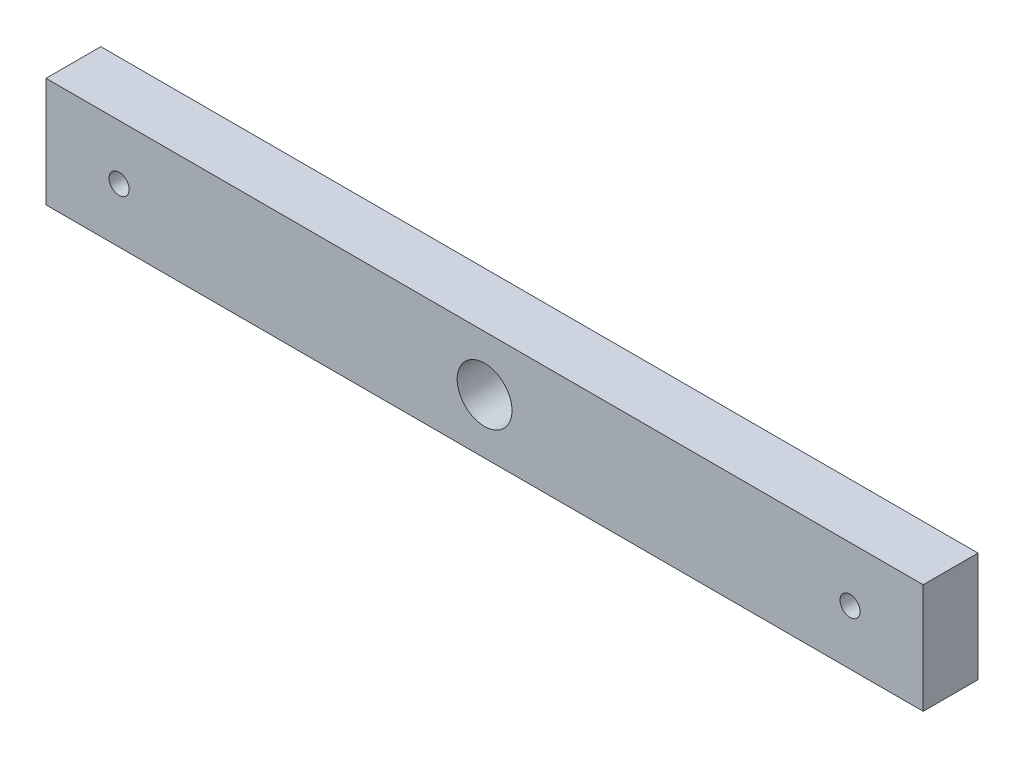
SolidWorks part; units mm, degrees
ref_plane "Plano frontal" through (0, 0, 0) normal (0, 0, 1) x (1, 0, 0)
ref_plane "Plano superior" through (0, 0, 0) normal (0, 1, 0) x (1, 0, 0)
ref_plane "Plano direito" through (0, 0, 0) normal (1, 0, 0) x (0, 0, -1)
sketch "Esboço1" plane through (0, 0, 0) normal (0, 0, 1) x (1, 0, 0)
  line L0 (100, 0) -> (-100, 0)
  line L2 (-100, 30) -> (100, 30)
  line L3 (-100, 30) -> (-120, 30)
  line L4 (-120, 30) -> (-120, 0)
  line L5 (-120, 0) -> (-100, 0)
  line L6 (100, 30) -> (120, 30)
  line L7 (120, 30) -> (120, 0)
  line L8 (100, 0) -> (120, 0)
  point P4 (0, 0)
  dimension "D1" = 30
  dimension "D2" = 20
  dimension "D3" = 20
extrude "Ressalto-extrusão1" add sketch "Esboço1" along normal blind 15
sketch "Esboço2" plane through (0, 0, 15) normal (0, 0, 1) x (1, 0, 0)
  line L0 (0, 30) -> (0, 0)
  line L1 (120, 30) -> (-120, 30) construction
  circle A0 centre (0, 15) radius 7.5
  dimension "D1" = 15
extrude "Corte-extrusão1" cut sketch "Esboço2" against normal blind 15 contours L0 A0 | L0 A0
sketch "Esboço3" plane through (0, 0, 15) normal (0, 0, 1) x (1, 0, 0)
  line L0 (0, 15) -> (-100, 15)
  line L1 (0, 15) -> (0, 30)
  line L2 (120, 30) -> (-120, 30) construction
  circle A0 centre (-100, 15) radius 2.75
  circle A1 centre (100, 15) radius 2.75
  dimension "D2" = 5.5
  dimension "D1" = 100
extrude "Corte-extrusão2" cut sketch "Esboço3" against normal blind 50
